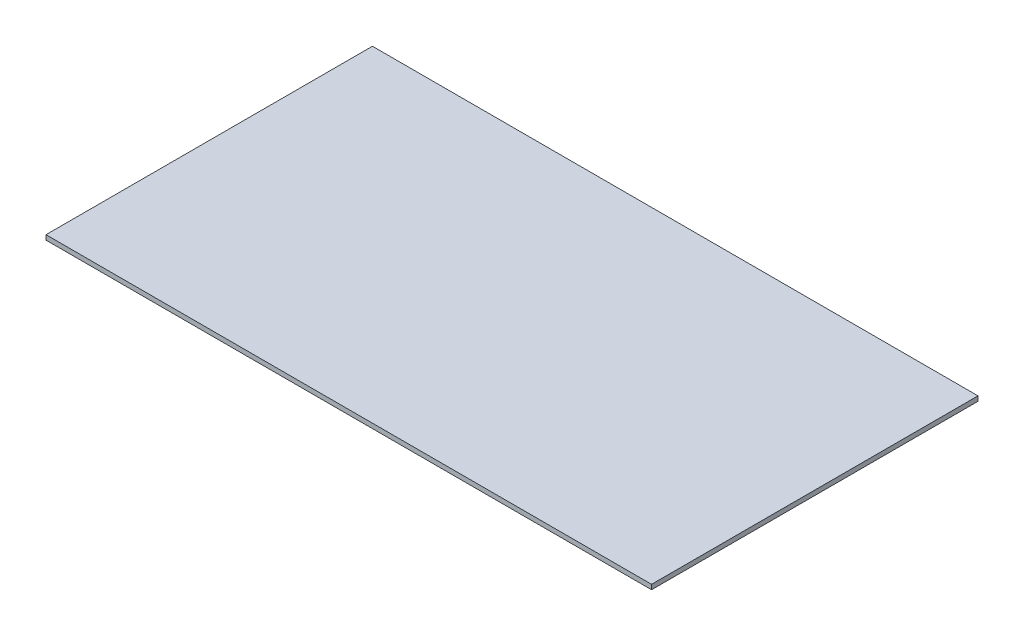
SolidWorks part; units mm, degrees
ref_plane "Front Plane" through (0, 0, 0) normal (0, 0, 1) x (1, 0, 0)
ref_plane "Top Plane" through (0, 0, 0) normal (0, 1, 0) x (1, 0, 0)
ref_plane "Right Plane" through (0, 0, 0) normal (1, 0, 0) x (0, 0, -1)
sketch "Sketch1" plane through (0, 0, 0) normal (0, 1, 0) x (1, 0, 0)
  line L0 (812.8, 3.175) -> (812.8, 434.975) construction
  line L1 (0, 0) -> (812.8, 0)
  line L2 (0, 0) -> (0, 438.15)
  line L3 (0, 438.15) -> (812.8, 438.15)
  line L4 (812.8, 0) -> (812.8, 438.15)
  line L5 (785.749, 438.15) -> (812.8, 438.15) construction
  point P5 (0, 415.623)
  point P6 (752.1492, 428.4038)
extrude "Boss-Extrude1" add sketch "Sketch1" along normal blind 6.35
